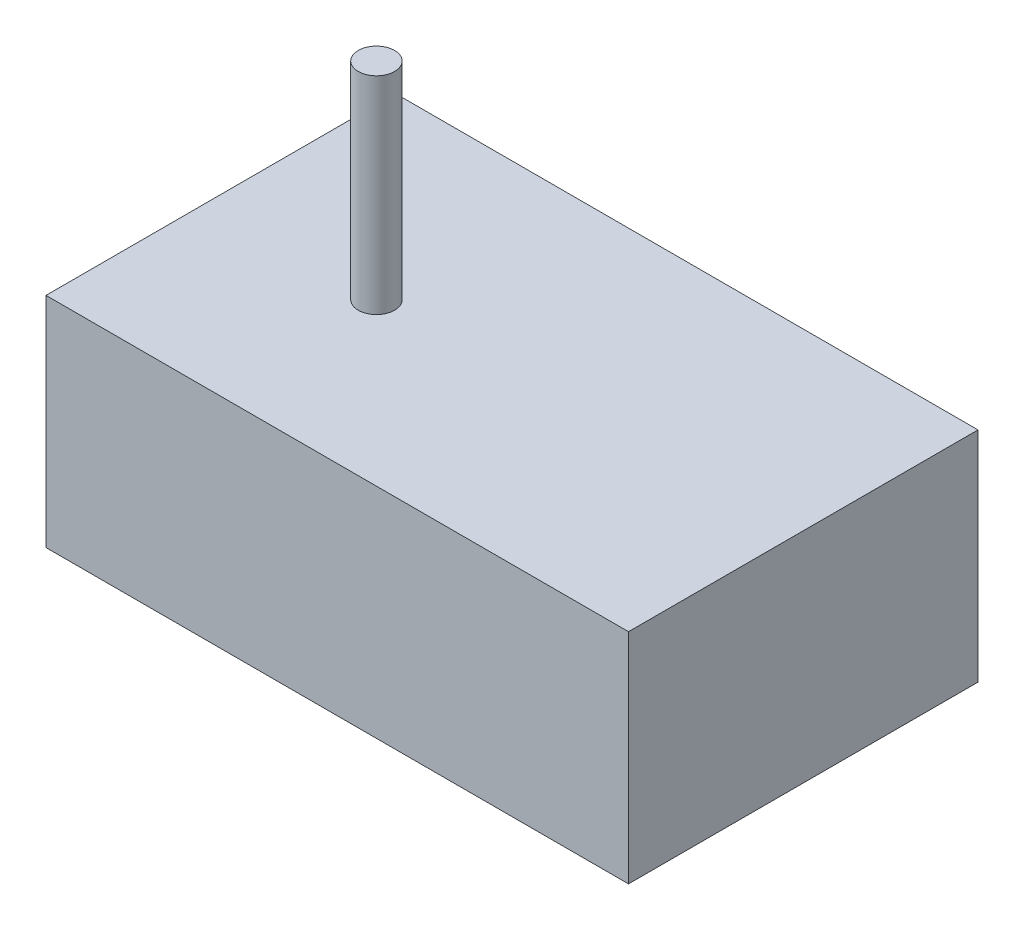
SolidWorks part; units mm, degrees
ref_plane "Front Plane" through (0, 0, 0) normal (0, 0, 1) x (1, 0, 0)
ref_plane "Top Plane" through (0, 0, 0) normal (0, 1, 0) x (1, 0, 0)
ref_plane "Right Plane" through (0, 0, 0) normal (1, 0, 0) x (0, 0, -1)
sketch "Sketch1" plane through (0, 0, 0) normal (0, 1, 0) x (1, 0, 0)
  line L1 (50.8, -30.48) -> (-50.8, -30.48)
  line L2 (50.8, -30.48) -> (50.8, 30.48)
  line L3 (50.8, 30.48) -> (-50.8, 30.48)
  line L4 (-50.8, -30.48) -> (-50.8, 30.48)
  line L5 (50.8, -30.48) -> (-50.8, 30.48) construction
  line L6 (50.8, 30.48) -> (-50.8, -30.48) construction
  circle A0 centre (-31.75, -2.54) radius 3.175
  point P0 (0, 0)
  dimension "D5" = 6.35
  dimension "D1" = 101.6
  dimension "D2" = 60.96
  dimension "D3" = 19.05
  dimension "D4" = 27.94
extrude "Boss-Extrude1" add sketch "Sketch1" along normal blind 2.54
sketch "Sketch2" plane through (0, 2.54, 0) normal (0, 1, 0) x (1, 0, 0)
  circle A0 centre (-0.0875, 0.4568) radius 3.1973
extrude "Cut-Extrude1" cut sketch "Sketch2" against normal blind 2.54
sketch "Sketch3" plane through (0, 2.54, 0) normal (0, 1, 0) x (1, 0, 0)
  circle A0 centre (-0.0875, 0.4568) radius 3.1973
extrude "Boss-Extrude2" add sketch "Sketch3" along normal blind 30.48 and the other way blind 5.08
sketch "Sketch6" plane through (0, 2.54, 0) normal (0, 1, 0) x (1, 0, 0)
  line L0 (-50.8, 30.48) -> (-50.8, -30.48) construction
  line L1 (-50.8, 33.02) -> (50.8, 33.02)
  line L2 (-50.8, 33.02) -> (-50.8, -33.02)
  line L3 (-50.8, -33.02) -> (50.8, -33.02)
  line L4 (50.8, 33.02) -> (50.8, -33.02)
  line L5 (50.8, -30.48) -> (50.8, 30.48) construction
  line L6 (50.8, 30.48) -> (-50.8, 30.48) construction
  line L7 (-50.8, -30.48) -> (50.8, -30.48) construction
  line L8 (-48.26, 30.48) -> (-48.26, -30.48)
  line L9 (48.26, 30.48) -> (48.26, -30.48)
  line L10 (-48.26, 30.48) -> (48.26, 30.48)
  line L11 (-48.26, -30.48) -> (48.26, -30.48)
  line L12 (-48.26, 30.48) -> (-48.26, 34.7818)
  line L13 (-48.26, -30.48) -> (-48.26, -35.4132)
  line L14 (48.26, -30.48) -> (48.26, -34.249)
  line L15 (48.26, -34.249) -> (48.26, 34.7818)
  line L16 (-48.26, 30.48) -> (-50.8, 30.48)
  line L17 (-50.8, 30.48) -> (-50.8, -30.48)
  line L18 (-50.8, -30.48) -> (-48.26, -30.48)
  line L19 (50.8, -30.48) -> (48.26, -30.48)
  line L20 (50.8, 30.48) -> (48.26, 30.48)
  line M8 (-50.8, 30.48) -> (-50.8, -30.48)
  line M9 (-50.8, -30.48) -> (50.8, -30.48)
  line M10 (50.8, -30.48) -> (50.8, 30.48)
  line M11 (50.8, 30.48) -> (-50.8, 30.48)
  dimension "D1" = 2.54
  dimension "D2" = 2.54
  dimension "D3" = 2.54
  dimension "D4" = 2.54
extrude "Boss-Extrude10" add sketch "Sketch6" along normal blind 33.02 contours L8 M11 M8 M9 | L9 M11 M9 M10 | L14 L15
sketch "Sketch7" plane through (0, 2.54, 0) normal (0, 1, 0) x (1, 0, 0)
  line L0 (48.26, 30.48) -> (48.26, -30.48) construction
  line L1 (-48.26, 30.48) -> (48.26, 30.48)
  line L2 (-48.26, 30.48) -> (-48.26, 27.94)
  line L3 (-48.26, 27.94) -> (48.26, 27.94)
  line L4 (48.26, 30.48) -> (48.26, 27.94)
  line L5 (-48.26, 30.48) -> (-48.26, -30.48) construction
  line L6 (48.26, -30.48) -> (-48.26, -30.48)
  line L7 (48.26, -30.48) -> (48.26, -27.94)
  line L8 (48.26, -27.94) -> (-48.26, -27.94)
  line L9 (-48.26, -30.48) -> (-48.26, -27.94)
  dimension "D1" = 2.54
  dimension "D2" = 2.54
extrude "Boss-Extrude11" add sketch "Sketch7" along normal blind 33.02
ref_plane "Plane1" through (-50.8, 35.56, -30.48) normal (0, 0, 1) x (1, 0, 0)
sketch "Sketch9" plane through (0, 35.56, 0) normal (0, 1, 0) x (1, 0, 0)
  line L1 (50.8, -30.48) -> (-50.8, -30.48)
  line L2 (50.8, -30.48) -> (50.8, 30.48)
  line L3 (50.8, 30.48) -> (-50.8, 30.48)
  line L4 (-50.8, -30.48) -> (-50.8, 30.48)
  point P6 (0, 0)
  point P7 (50.8, -30.48)
extrude "Boss-Extrude12" add sketch "Sketch9" along normal blind 2.54
sketch "Sketch10" plane through (0, 38.1, 0) normal (0, 1, 0) x (1, 0, 0)
  circle A0 centre (-21.3251, -2.32) radius 3.175 construction
  circle A1 centre (-21.3251, -2.32) radius 3.175
  point P0 (-21.3251, -2.32)
  dimension "D1" = 6.35
extrude "Boss-Extrude13" add sketch "Sketch10" along normal blind 36.068 and the other way blind 12.7
